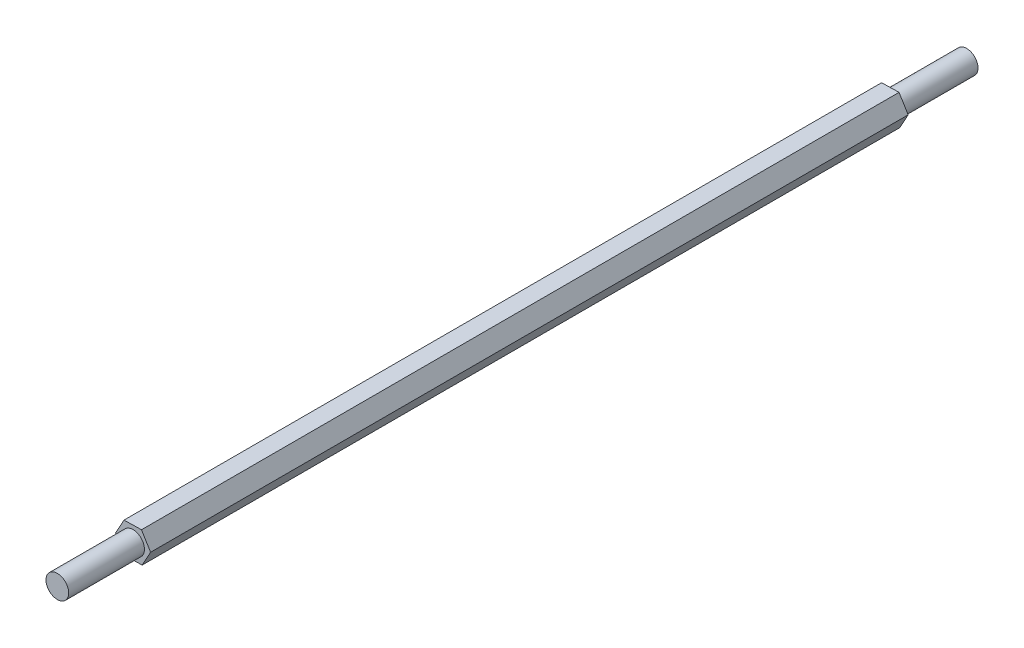
SolidWorks part; units mm, degrees
ref_plane "Front Plane" through (0, 0, 0) normal (0, 0, 1) x (1, 0, 0)
ref_plane "Top Plane" through (0, 0, 0) normal (0, 1, 0) x (1, 0, 0)
ref_plane "Right Plane" through (0, 0, 0) normal (1, 0, 0) x (0, 0, -1)
sketch "Sketch2" plane through (0, 0, 0) normal (0, 0, 1) x (1, 0, 0)
  line L1 (-18.5759, 5.5468) -> (-20.8847, 5.496)
  line L2 (-20.8847, 5.496) -> (-21.9952, 3.4711)
  line L3 (-21.9952, 3.4711) -> (-20.7968, 1.497)
  line L4 (-20.7968, 1.497) -> (-18.4879, 1.5477)
  line L5 (-18.4879, 1.5477) -> (-17.3775, 3.5727)
  line L6 (-17.3775, 3.5727) -> (-18.5759, 5.5468)
  circle A0 centre (-19.6863, 3.5219) radius 2 construction
extrude "Boss-Extrude1" add sketch "Sketch2" along normal blind 100
sketch "Sketch3" plane through (0, 0, 100) normal (0, 0, 1) x (1, 0, 0)
  circle A0 centre (-19.6839, 3.5058) radius 1.5
extrude "Boss-Extrude2" add sketch "Sketch3" along normal blind 10
sketch "Sketch4" plane through (0, 0, 0) normal (0, 0, -1) x (-1, 0, 0)
  circle A0 centre (19.6538, 3.5325) radius 1.5
extrude "Boss-Extrude3" add sketch "Sketch4" along normal blind 10
